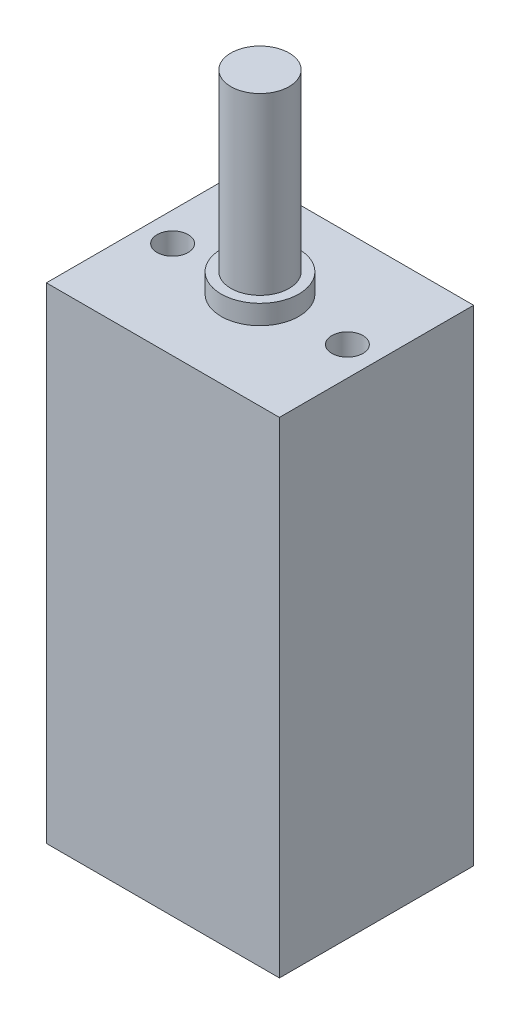
SolidWorks part; units mm, degrees
ref_plane "前视基准面" through (0, 0, 0) normal (0, 0, 1) x (1, 0, 0)
ref_plane "上视基准面" through (0, 0, 0) normal (0, 1, 0) x (1, 0, 0)
ref_plane "右视基准面" through (0, 0, 0) normal (1, 0, 0) x (0, 0, -1)
sketch "草图1" plane through (0, 0, 0) normal (0, 1, 0) x (1, 0, 0)
  line L1 (-6, 5) -> (6, 5)
  line L2 (-6, 5) -> (-6, -5)
  line L3 (-6, -5) -> (6, -5)
  line L4 (6, 5) -> (6, -5)
  line L5 (-6, 5) -> (6, -5) construction
  line L6 (-6, -5) -> (6, 5) construction
  point P0 (0, 0)
  dimension "D1" = 10
  dimension "D2" = 12
extrude "凸台-拉伸1" add sketch "草图1" along normal blind 25
sketch "草图2" plane through (0, 25, 0) normal (0, 1, 0) x (1, 0, 0)
  circle A0 centre (0, 0) radius 2
  dimension "D1" = 4
extrude "凸台-拉伸2" add sketch "草图2" along normal blind 1
sketch "草图3" plane through (0, 26, 0) normal (0, 1, 0) x (1, 0, 0)
  circle A0 centre (0, 0) radius 1.5
  dimension "D1" = 3
extrude "凸台-拉伸3" add sketch "草图3" along normal blind 9
sketch "草图4" plane through (0, 25, 0) normal (0, 1, 0) x (1, 0, 0)
  line L0 (-4.5, 0) -> (4.5, 0) construction
  circle A0 centre (-4.5, 0) radius 0.8
  circle A1 centre (4.5, 0) radius 0.8
  point P4 (0, 0)
  dimension "D2" = 1.6
  dimension "D1" = 9
extrude "切除-拉伸1" cut sketch "草图4" against normal blind 5
